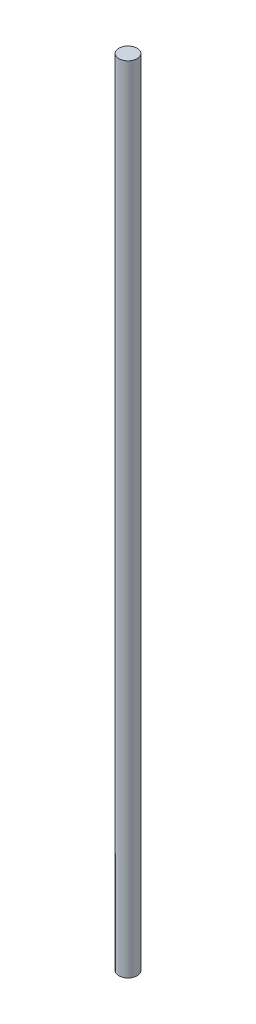
SolidWorks part; units mm, degrees
ref_plane "Front Plane" through (0, 0, 0) normal (0, 0, 1) x (1, 0, 0)
ref_plane "Top Plane" through (0, 0, 0) normal (0, 1, 0) x (1, 0, 0)
ref_plane "Right Plane" through (0, 0, 0) normal (1, 0, 0) x (0, 0, -1)
sketch "Sketch1" plane through (0, 0, 0) normal (0, 1, 0) x (1, 0, 0)
  circle A0 centre (0, 0) radius 4.2
  dimension "D1" = 8.4
extrude "Boss-Extrude1" add sketch "Sketch1" along normal blind 366.8
